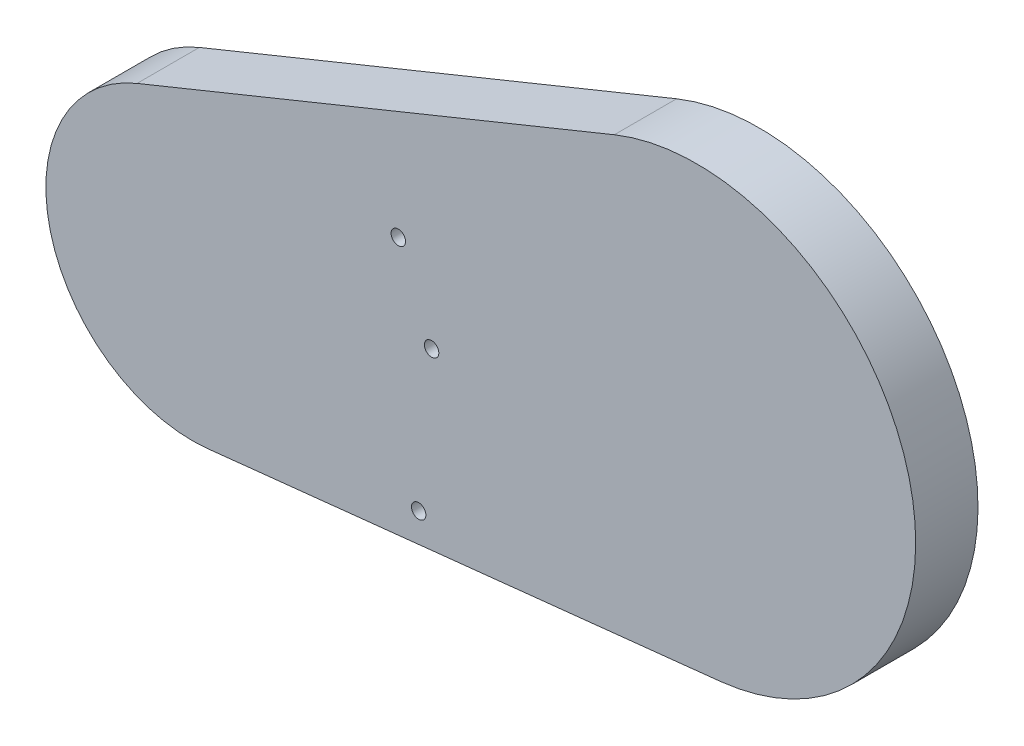
SolidWorks part; units mm, degrees
ref_plane "Front Plane" through (0, 0, 0) normal (0, 0, 1) x (1, 0, 0)
ref_plane "Top Plane" through (0, 0, 0) normal (0, 1, 0) x (1, 0, 0)
ref_plane "Right Plane" through (0, 0, 0) normal (1, 0, 0) x (0, 0, -1)
sketch "Sketch1" plane through (0, 0, 0) normal (0, 0, 1) x (1, 0, 0)
  line L0 (-196.7367, -55.8663) -> (-222.1367, -55.8663) construction
  line L1 (-246.406, 3.7881) -> (-36.314, 89.2603)
  line L2 (10.2328, -95.8196) -> (-215.2979, -119.9044)
  line L3 (-236.8343, -19.7394) -> (-26.7422, 65.7328) construction
  line L4 (8.4781, -70.4562) -> (-192.0771, -94.5892) construction
  line L5 (-213.1234, -20.4735) -> (-29.8155, 64.3971) construction
  line L6 (-217.9951, -94.648) -> (7.5356, -70.5632) construction
  line L7 (14.8118, -67.1357) -> (-211.32, -94.3464) construction
  line L8 (15.4187, -72.1793) -> (-210.7131, -99.39) construction
  line L9 (-184.0526, -93.5777) -> (7.8053, -73.0888) construction
  line L10 (-184.592, -88.5264) -> (7.2659, -68.0376) construction
  line L11 (-229.2044, -19.3775) -> (-25.785, 63.3801) construction
  line L12 (-231.1188, -14.672) -> (-27.6994, 68.0856) construction
  line L13 (-203.5832, -18.8555) -> (-28.7483, 62.0921) construction
  line L14 (-205.7175, -14.2456) -> (-30.8827, 66.702) construction
  line L15 (15.1153, -69.6575) -> (-211.0166, -96.8682) construction
  line L16 (-184.3223, -91.0521) -> (7.5356, -70.5632) construction
  line L17 (-204.6504, -16.5505) -> (-29.8155, 64.3971) construction
  line L18 (-230.1616, -17.0247) -> (-26.7422, 65.7328) construction
  circle A0 centre (-196.7367, -55.8663) radius 39.0022 construction
  circle A1 centre (-196.7367, -55.8663) radius 64.4022 construction
  arc A2 (-246.406, 3.7881) -> (-215.2979, -119.9044) centre (-222.1367, -55.8663) ccw
  circle A3 centre (0, 0) radius 70.9644 construction
  arc A4 (10.2328, -95.8196) -> (-36.314, 89.2603) centre (0, 0) ccw
  arc A5 (-157.7345, -55.8663) -> (-209.4367, 7.2713) centre (-222.1367, -55.8663) ccw construction
  arc A6 (-36.314, 89.2603) -> (10.2328, -95.8196) centre (0, 0) ccw construction
  circle A7 centre (0, 0) radius 96.3644 construction
  arc A8 (-209.4367, -119.0039) -> (-157.7345, -55.8663) centre (-222.1367, -55.8663) ccw construction
  arc A9 (-209.4367, 7.2713) -> (-246.406, 3.7881) centre (-222.1367, -55.8663) ccw construction
  arc A10 (-215.2979, -119.9044) -> (-209.4367, -119.0039) centre (-222.1367, -55.8663) ccw construction
  circle A11 centre (-131.3865, 2.594) radius 3.175
  circle A12 centre (-116.7292, -32.5753) radius 3.175
  circle A13 centre (-122.419, -97.2135) radius 3.175
  circle A14 centre (-222.1367, -55.8663) radius 107.95 construction
  circle A15 centre (-222.1367, -55.8663) radius 39.0022 construction
  dimension "D1" = 25.4
  dimension "D3" = 25.4
  dimension "D4" = 6.35
  dimension "D5" = 12.7
  dimension "D8" = 215.9
  dimension "D2" = 25.4
  dimension "D6" = 44.45
  dimension "D7" = 82.55
  dimension "D9" = 2.54
  dimension "D10" = 2.54
  dimension "D11" = 2.54
  dimension "D12" = 2.54
  dimension "D13" = 2.54
  dimension "D14" = 2.54
  dimension "D15" = 2.54
  dimension "D16" = 2.54
extrude "Boss-Extrude1" add sketch "Sketch1" along normal offset from surface (27.435 mm away) 12.7
shell "Shell1" thickness 2.54
sketch "Sketch2" plane through (0, 0, 0) normal (0, 1, 0) x (1, 0, 0)
  line L0 (-36.314, 0) -> (-246.406, 0) construction
  line L1 (-35.3568, 0) -> (-245.4488, 0) construction
  line L2 (-127, 0) -> (76.2, 0)
  arc A0 (-127, 0) -> (76.2, 0) centre (-25.4, 104.9192) ccw
  dimension "D1" = 146.05
  dimension "D2" = 203.2
  dimension "D3" = 127
extrude "Cut-Extrude1" [suppressed] cut sketch "Sketch2" along normal through all
